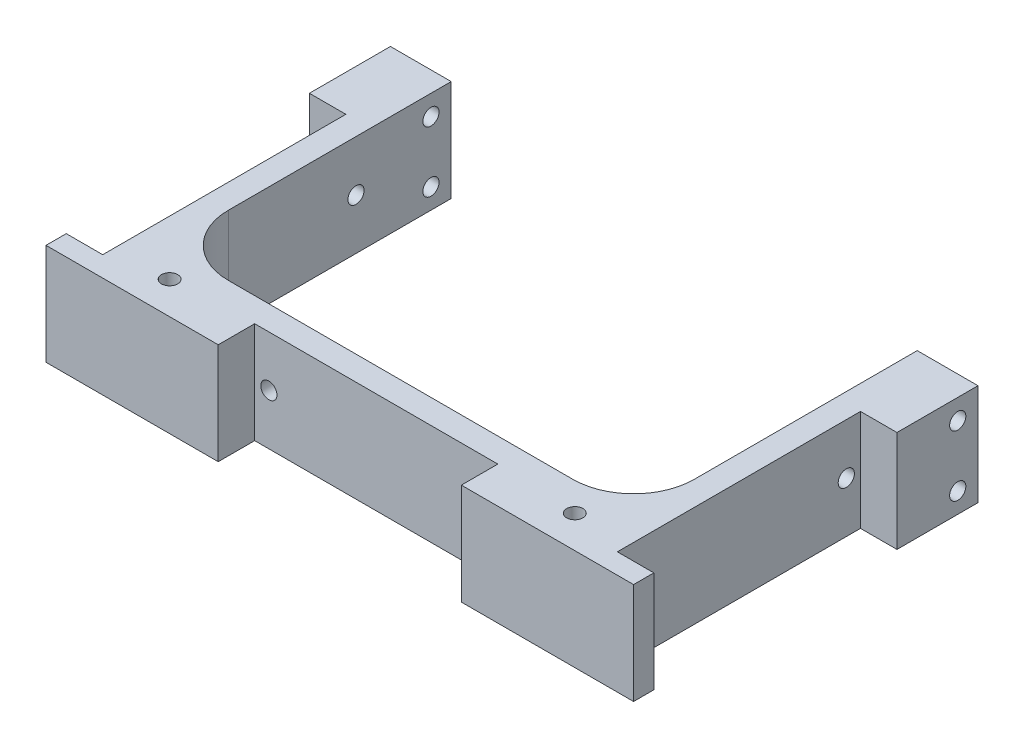
SolidWorks part; units mm, degrees
ref_plane "Front" through (0, 0, 0) normal (0, 0, 1) x (1, 0, 0)
ref_plane "Top" through (0, 0, 0) normal (0, 1, 0) x (1, 0, 0)
ref_plane "Right" through (0, 0, 0) normal (1, 0, 0) x (0, 0, -1)
sketch "Sketch1" plane through (0, 0, 0) normal (0, 1, 0) x (1, 0, 0)
  line L0 (-72.5, 35) -> (-72.5, 15)
  line L1 (-72.5, -50) -> (-30, -50)
  line L2 (72.5, -50) -> (72.5, -45)
  line L3 (-57.5, 35) -> (-57.5, -35)
  line L4 (-57.5, -35) -> (57.5, -35)
  line L5 (57.5, -35) -> (57.5, 35)
  line L6 (-72.5, 35) -> (-57.5, 35)
  line L7 (57.5, 35) -> (72.5, 35)
  line L8 (-57.5, 0) -> (57.5, 0) construction
  line L13 (-50.8, 25.4) -> (50.8, -25.4) construction
  line L14 (-30, -50) -> (-30, -41)
  line L15 (-30, -41) -> (30, -41)
  line L16 (30, -41) -> (30, -50)
  line L17 (0, 0) -> (0, -50) construction
  line L18 (30, -50) -> (72.5, -50)
  line L19 (-30, -50) -> (30, -50) construction
  line L20 (-72.5, -45) -> (-72.5, -50)
  line L21 (-72.5, 15) -> (-63.5, 15)
  line L23 (-72.5, -45) -> (-63.5, -45)
  line L24 (-63.5, 15) -> (-63.5, -45)
  line L25 (-72.5, 15) -> (-72.5, -45) construction
  line L26 (-72.5, -15) -> (-63.5, -15) construction
  line L27 (72.5, 15) -> (72.5, 35)
  line L28 (72.5, 15) -> (63.5, 15)
  line L30 (72.5, -45) -> (63.5, -45)
  line L31 (63.5, 15) -> (63.5, -45)
  line L32 (72.5, 35) -> (72.5, -50) construction
  point P29 (-68, -45)
  line B0 (-50.8, 25.4) -> (50.8, 25.4) construction
  line B1 (-50.8, 25.4) -> (-50.8, -25.4) construction
  line B2 (-50.8, -25.4) -> (50.8, -25.4) construction
  line B3 (50.8, 25.4) -> (50.8, -25.4) construction
  dimension "D1" = 115
  dimension "D2" = 15
  dimension "D3" = 60
  dimension "D4" = 60
  dimension "D5" = 15
  dimension "D6" = 9
  dimension "D7" = 20
  dimension "D8" = 5
sketch_block_instance "Block1-1"
sketch_block "Block1" parameters "D1"=101.6, "D2"=50.8
extrude "Boss-Extrude1" add sketch "Sketch1" along normal blind 25 contours L31 L28 L27 L7 L5 L4 L3 L6 L0 L21 L24 L23 L20 L1 L14 L15 L16 L18 L2 L30
sketch "Sketch2" plane through (0, 0, 41) normal (0, 0, 1) x (1, 0, 0)
  line L0 (30, 12.5) -> (-30, 12.5) construction
  line L1 (30, 25) -> (30, 0) construction
  line L2 (-30, 25) -> (-30, 0) construction
  line L3 (0, 0) -> (0, 25) construction
  line L4 (-30, 25) -> (30, 25) construction
  circle A0 centre (-26.5, 12.5) radius 2
  circle A1 centre (26.5, 12.5) radius 2
  dimension "D2" = 4
  dimension "D1" = 53
extrude "Cut-Extrude1" cut sketch "Sketch2" against normal up to surface (6 mm away) up to face at (0, 12.5, 35)
sketch "Sketch3" plane through (-63.5, 0, 0) normal (-1, 0, 0) x (0, 0, 1)
  line L0 (-15, 12.5) -> (45, 12.5) construction
  line L1 (-15, 25) -> (-15, 0) construction
  line L2 (45, 25) -> (45, 0) construction
  line L3 (15, 0) -> (15, 25) construction
  line L4 (-15, 0) -> (45, 0) construction
  line L5 (-15, 25) -> (45, 25) construction
  circle A0 centre (-11.5, 12.5) radius 2
  circle A1 centre (41.5, 12.5) radius 2
  dimension "D2" = 4
  dimension "D1" = 53
extrude "Cut-Extrude2" cut sketch "Sketch3" against normal blind 7
sketch "Sketch10" plane through (63.5, 0, 0) normal (1, 0, 0) x (0, 0, -1)
  line L0 (-41.5, 12.5) -> (11.5, 12.5) construction
  line L1 (-45, 0) -> (15, 0) construction
  line L2 (-15, 0) -> (-15, 25) construction
  line L3 (15, 25) -> (-45, 25) construction
  circle A0 centre (-41.5, 12.5) radius 2
  circle A1 centre (11.5, 12.5) radius 2
  point P14 (-15, 12.5)
  dimension "D1" = 4
  dimension "D2" = 53
extrude "Cut-Extrude3" cut sketch "Sketch10" against normal blind 7
fillet "Fillet1" radius 15 2 edges at (57.5, 12.5, 35) (-57.5, 12.5, 35)
sketch "Sketch13" plane through (-72.5, 0, 0) normal (-1, 0, 0) x (0, 0, 1)
  line L0 (-25, 0) -> (-25, 25) construction
  line L1 (-35, 0) -> (-15, 0) construction
  line L2 (-35, 25) -> (-15, 25) construction
  line L3 (-25, 0) -> (-35, 0) construction
  line L4 (-30, 0) -> (-30, 25) construction
  line L5 (-25, 12.5) -> (-35, 12.5) construction
  line L6 (-35, 25) -> (-35, 0) construction
  circle A0 centre (-30, 20) radius 2
  circle A1 centre (-30, 5) radius 2
  dimension "D2" = 4
  dimension "D1" = 15
extrude "Cut-Extrude6" cut sketch "Sketch13" against normal through all
sketch "Sketch14" plane through (0, 25, 0) normal (0, 1, 0) x (1, 0, 0)
  line L0 (-50, -42) -> (50, -42) construction
  line L1 (0, -42) -> (0, 0) construction
  line L2 (-72.5, -50) -> (-30, -50) construction
  circle A0 centre (50, -42) radius 2
  circle A1 centre (-50, -42) radius 2
  dimension "D2" = 4
  dimension "D1" = 100
  dimension "D3" = 8
extrude "Cut-Extrude7" cut sketch "Sketch14" against normal through all
